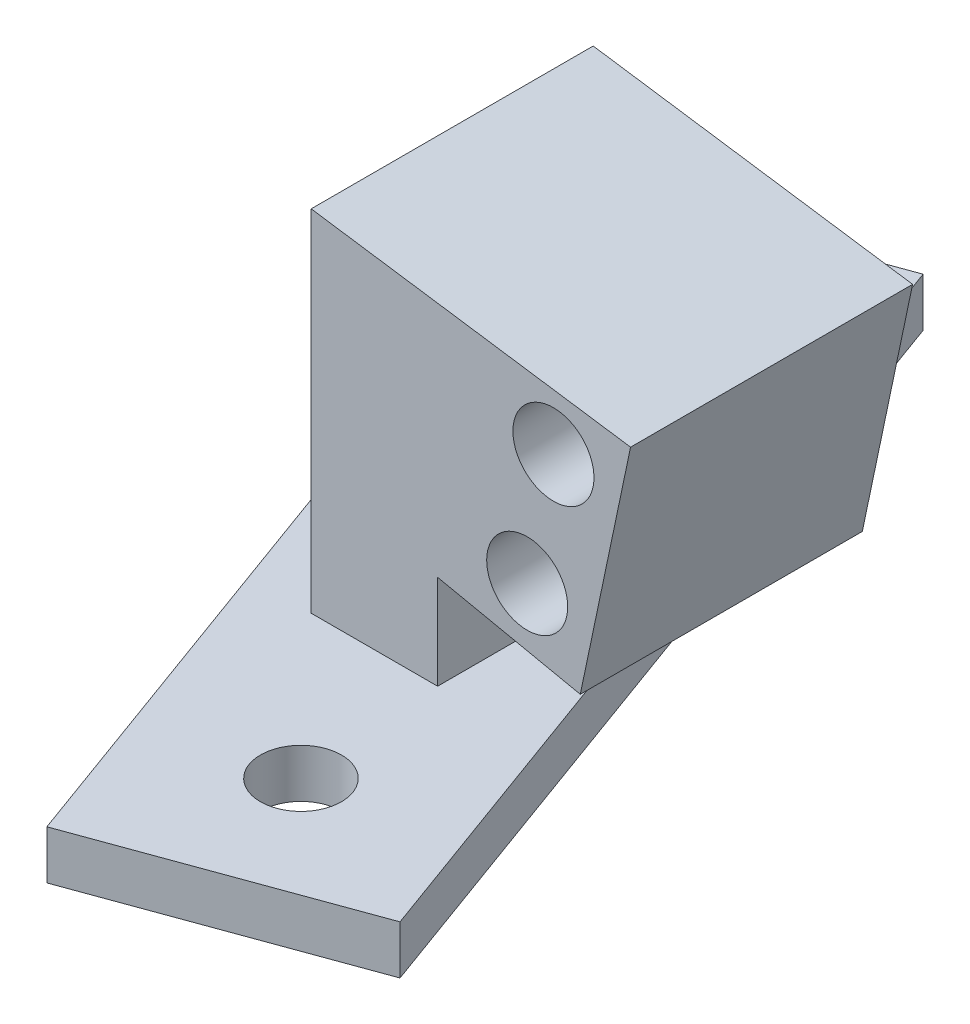
SolidWorks part; units mm, degrees
ref_plane "Front Plane" through (0, 0, 0) normal (0, 0, 1) x (1, 0, 0)
ref_plane "Top Plane" through (0, 0, 0) normal (0, 1, 0) x (1, 0, 0)
ref_plane "Right Plane" through (0, 0, 0) normal (1, 0, 0) x (0, 0, -1)
sketch "Sketch1" plane through (0, 0, 0) normal (0, 0, 1) x (1, 0, 0)
  line L0 (-629.0113, 228.5148) -> (-646.4173, 232.1744)
  line L1 (-625.5069, 227.7779) -> (-640.2031, 230.8679) construction
  line L2 (-646.4173, 232.1744) -> (-650.3578, 213.4325)
  line L3 (-650.3578, 213.4325) -> (-632.9518, 209.7729)
  line L4 (-626.0822, 208.3286) -> (-644.038, 212.1038) construction
  line L5 (-632.9518, 209.7729) -> (-629.0113, 228.5148)
  circle A0 centre (-635.0536, 225) radius 3.175
  circle A1 centre (-637.1112, 215.214) radius 3.175
  dimension "D4" = 6.35
  dimension "D5" = 6.35
  dimension "D1" = 6.35
  dimension "D2" = 19.1516
  dimension "D3" = 17.7865
extrude "Boss-Extrude1" add sketch "Sketch1" along normal up to surface (22.098 mm away)
sketch "Sketch2" plane through (15.4424, 73.4471, 0) normal (-0.2058, -0.9786, 0) x (0.9786, -0.2058, 0)
  line L0 (-680.3571, 22.098) -> (-680.3571, 0)
  line L1 (-680.3571, 0) -> (-673.9925, 0)
  line L2 (-680.3571, 0) -> (-662.5706, 0) construction
  line L3 (-673.9925, 0) -> (-673.9925, 22.098)
  line L4 (-662.5706, 22.098) -> (-680.3571, 22.098) construction
  line L5 (-673.9925, 22.098) -> (-680.3571, 22.098)
  dimension "D1" = 6.3646
extrude "Boss-Extrude2" add sketch "Sketch2" along normal blind 8.89 contours L5 L0 L1 L3
ref_plane "Plane5" through (0, 204.7328, 0) normal (0, 1, 0) x (1, 0, 0)
sketch "Sketch12" plane through (0, 204.7328, 0) normal (0, 1, 0) x (1, 0, 0)
  line L0 (-673.3567, 17.4995) -> (-649.901, -46.9446)
  line L1 (-649.901, -46.9446) -> (-629.613, -39.5604)
  line L2 (-629.613, -39.5604) -> (-653.0688, 24.8837)
  line L3 (-653.0688, 24.8837) -> (-673.3567, 17.4995)
  line L5 (-646.4173, -22.098) -> (-629.0113, -22.098) construction
  circle A0 centre (-659.7378, 11.6443) radius 3.175
  circle A1 centre (-643.2319, -33.7052) radius 3.175
  dimension "D5" = 10.16
  dimension "D7" = 6.35
  dimension "D10" = 6.35
  dimension "D2" = 110
  dimension "D3" = 6.35
  dimension "D4" = 24.13
  dimension "D6" = 10.795
  dimension "D8" = 10.795
  dimension "D9" = 10.16
  dimension "D11" = 68.58
  dimension "D12" = 21.59
extrude "Boss-Extrude6" add sketch "Sketch12" against normal blind 3.81
sketch "Sketch19" plane through (0, 0, 22.098) normal (0, 0, 1) x (1, 0, 0)
  line L0 (-646.4173, 232.1744) -> (-654.0373, 232.1744)
  line L1 (-654.0373, 232.1744) -> (-654.0373, 204.7328)
  line L2 (-673.3567, 204.7328) -> (-649.901, 204.7328) construction
  line L3 (-654.0373, 204.7328) -> (-652.1869, 204.7328)
  line L4 (-652.1869, 204.7328) -> (-646.4173, 232.1744)
  dimension "D1" = 7.62
extrude "Boss-Extrude12" add sketch "Sketch19" against normal up to surface (22.098 mm away) up to face at (-641.73, 215.3418, 0)
sketch "Sketch20" plane through (0, 0, 0) normal (0, 0, -1) x (-1, 0, 0)
  line L0 (629.0113, 228.5148) -> (654.0373, 232.1744)
  line L1 (654.0373, 232.1744) -> (646.4173, 232.1744)
  line L2 (646.4173, 232.1744) -> (629.0113, 228.5148)
extrude "Cut-Extrude1" cut sketch "Sketch20" against normal blind 35.052
sketch "Sketch21" plane through (0, 0, 0) normal (0, 0, -1) x (-1, 0, 0)
  line L0 (644.1294, 212.123) -> (644.1294, 204.7328)
  line L1 (419.4444, 204.7328) -> (-419.4444, 204.7328) construction
  line L2 (644.1294, 204.7328) -> (645.6832, 204.7328)
  line L3 (645.6832, 204.7328) -> (644.1294, 212.123) construction
  line L4 (645.6832, 204.7328) -> (644.1294, 212.123)
extrude "Boss-Extrude13" add sketch "Sketch21" against normal blind 22.098
